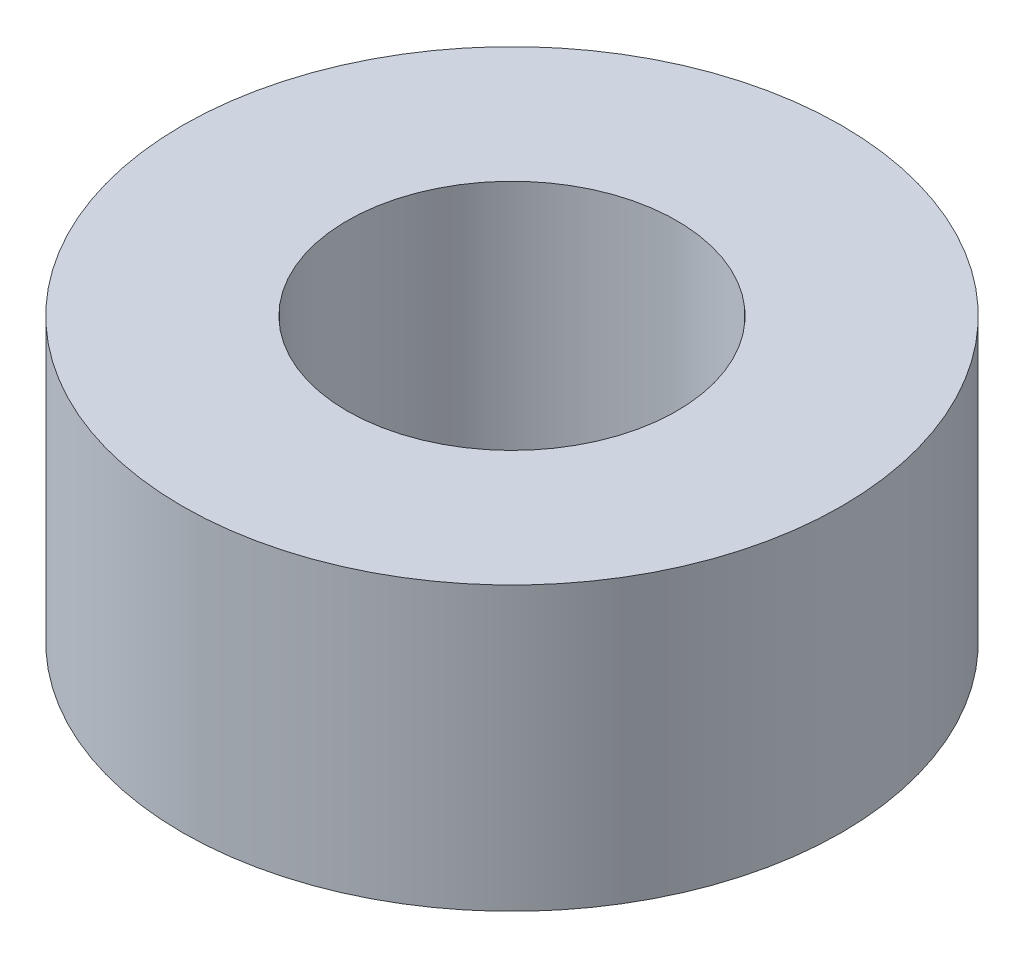
SolidWorks part; units mm, degrees
ref_plane "前视基准面" through (0, 0, 0) normal (0, 0, 1) x (1, 0, 0)
ref_plane "上视基准面" through (0, 0, 0) normal (0, 1, 0) x (1, 0, 0)
ref_plane "右视基准面" through (0, 0, 0) normal (1, 0, 0) x (0, 0, -1)
other "Configuration Table"
sketch "草图1" plane through (0, 0, 0) normal (0, 1, 0) x (1, 0, 0)
  circle A0 centre (0, 0) radius 3.5
  circle A1 centre (0, 0) radius 1.75
  dimension "D1" = 7
  dimension "D2" = 3.5
extrude "凸台-拉伸1" add sketch "草图1" along normal blind 3
